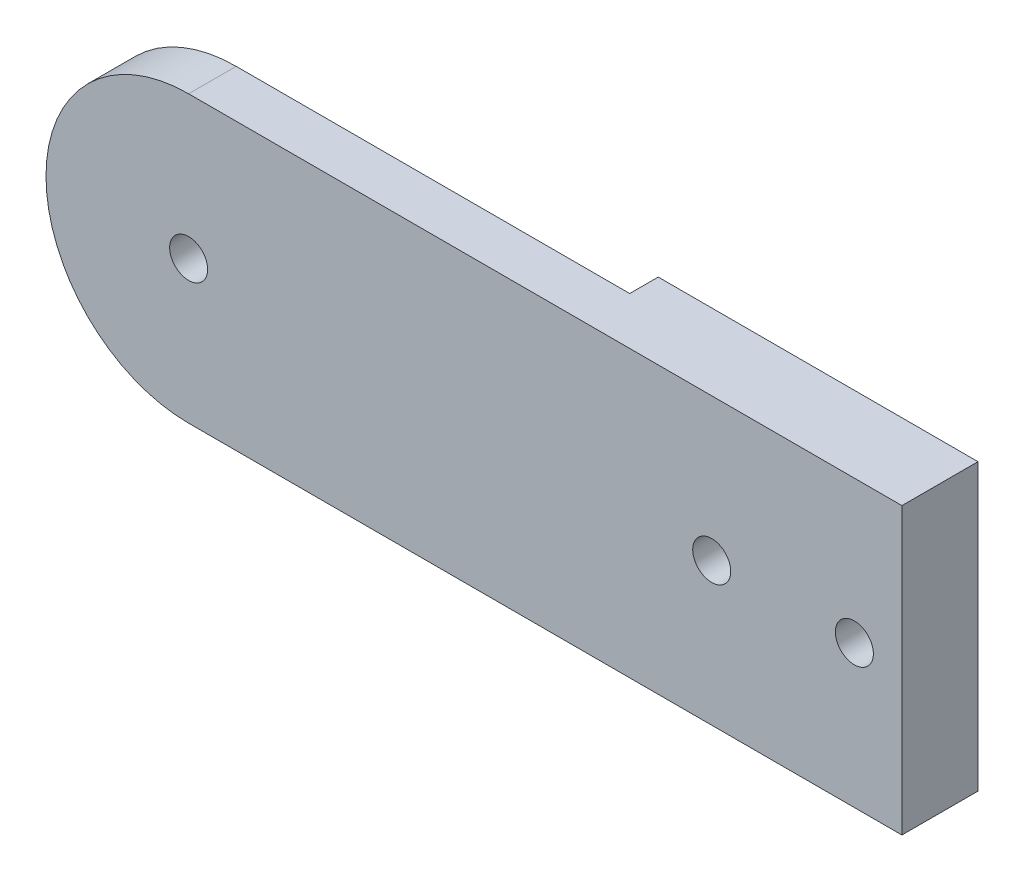
SolidWorks part; units mm, degrees
ref_plane "Front Plane" through (0, 0, 0) normal (0, 0, 1) x (1, 0, 0)
ref_plane "Top Plane" through (0, 0, 0) normal (0, 1, 0) x (1, 0, 0)
ref_plane "Right Plane" through (0, 0, 0) normal (1, 0, 0) x (0, 0, -1)
sketch "Sketch1" plane through (0, 0, 0) normal (0, 0, 1) x (1, 0, 0)
  line L1 (-30, 15) -> (45, 15)
  line L3 (-30, -15) -> (45, -15)
  line L4 (45, 15) -> (45, -15)
  line L5 (0, 0) -> (45, -15) construction
  line L6 (0, 0) -> (45, 15) construction
  arc A0 (-30, 15) -> (-30, -15) centre (-30, 0) ccw
  point P0 (0, 0)
extrude "Boss-Extrude2" add sketch "Sketch1" along normal blind 5
sketch "Sketch3" plane through (0, 0, 0) normal (0, 0, -1) x (-1, 0, 0)
  line L0 (-45, -15) -> (-45, 15) construction
  line L1 (-45, 15) -> (30, 15) construction
  circle A0 centre (-40, 0) radius 2
  circle A1 centre (-25, 0) radius 2
  dimension "D1" = 4
  dimension "D2" = 4
  dimension "D3" = 5
  dimension "D4" = 20
  dimension "D5" = 15
  dimension "D6" = 15
extrude "Cut-Extrude1" cut sketch "Sketch3" against normal through all
sketch "Sketch5" plane through (0, 0, 0) normal (0, 0, -1) x (-1, 0, 0)
  line L0 (30, -15) -> (-45, -15) construction
  line L1 (-45, 15) -> (-11.3769, 15)
  line L2 (-45, 15) -> (-45, -15)
  line L3 (-45, -15) -> (-11.3769, -15)
  line L4 (-11.3769, 15) -> (-11.3769, -15)
extrude "Boss-Extrude3" add sketch "Sketch5" along normal blind 3
sketch "Sketch6" plane through (0, 0, -3) normal (0, 0, -1) x (-1, 0, 0)
  line L0 (-45, 15) -> (-45, -15) construction
  circle A0 centre (-40, 0) radius 2
  circle A1 centre (-25, 0) radius 2
  dimension "D1" = 4
  dimension "D2" = 4
  dimension "D3" = 5
  dimension "D4" = 20
extrude "Cut-Extrude2" cut sketch "Sketch6" against normal blind 3
sketch "Sketch7" plane through (0, 0, 5) normal (0, 0, 1) x (1, 0, 0)
  line L0 (45, -15) -> (45, 15) construction
  circle A0 centre (-30, 0) radius 2
  dimension "D1" = 4
  dimension "D2" = 75
extrude "Cut-Extrude3" cut sketch "Sketch7" against normal through all
